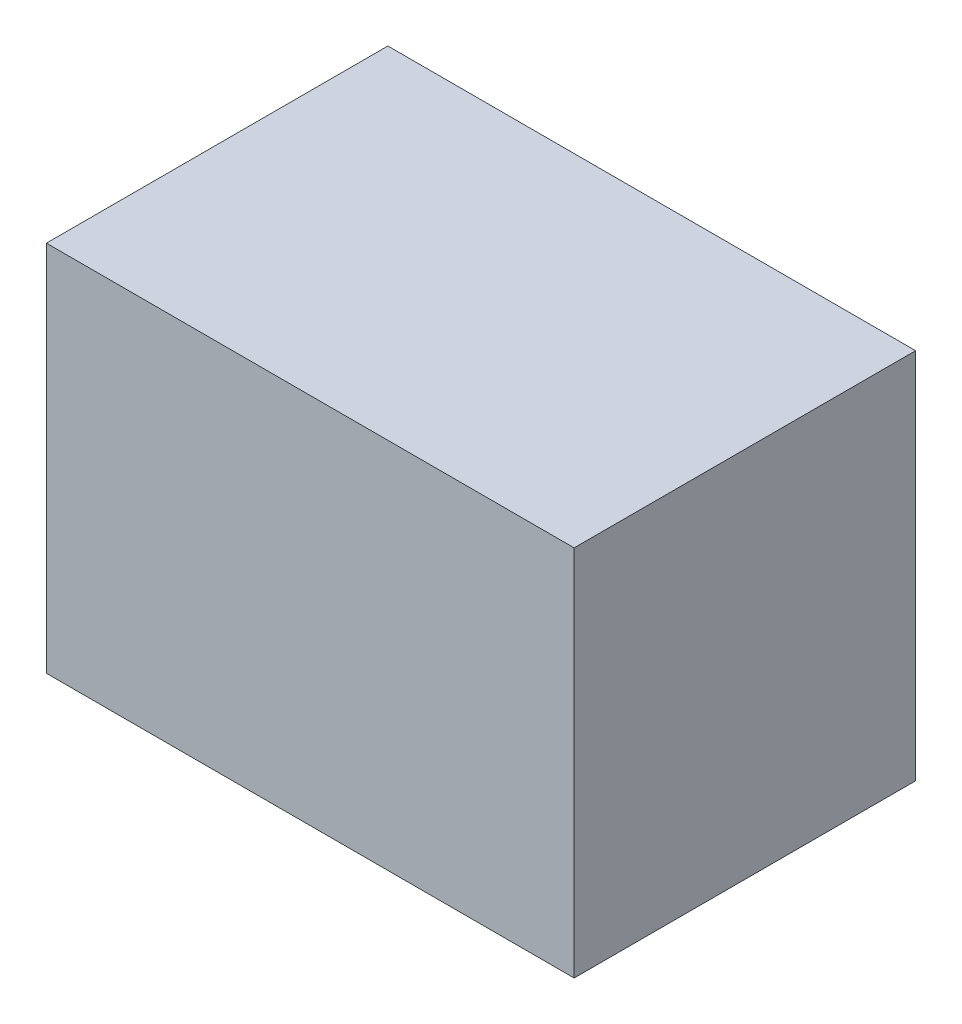
SolidWorks part; units mm, degrees
ref_plane "Front Plane" through (0, 0, 0) normal (0, 0, 1) x (1, 0, 0)
ref_plane "Top Plane" through (0, 0, 0) normal (0, 1, 0) x (1, 0, 0)
ref_plane "Right Plane" through (0, 0, 0) normal (1, 0, 0) x (0, 0, -1)
sketch "Sketch1" plane through (0, 0, 0) normal (0, 1, 0) x (1, 0, 0)
  line L1 (-26.9875, -17.4625) -> (26.9875, -17.4625)
  line L2 (-26.9875, -17.4625) -> (-26.9875, 17.4625)
  line L3 (-26.9875, 17.4625) -> (26.9875, 17.4625)
  line L4 (26.9875, -17.4625) -> (26.9875, 17.4625)
  line L5 (-26.9875, -17.4625) -> (26.9875, 17.4625) construction
  line L6 (-26.9875, 17.4625) -> (26.9875, -17.4625) construction
  point P0 (0, 0)
  dimension "D1" = 34.925
  dimension "D2" = 53.975
extrude "Boss-Extrude1" add sketch "Sketch1" along normal blind 38.1
